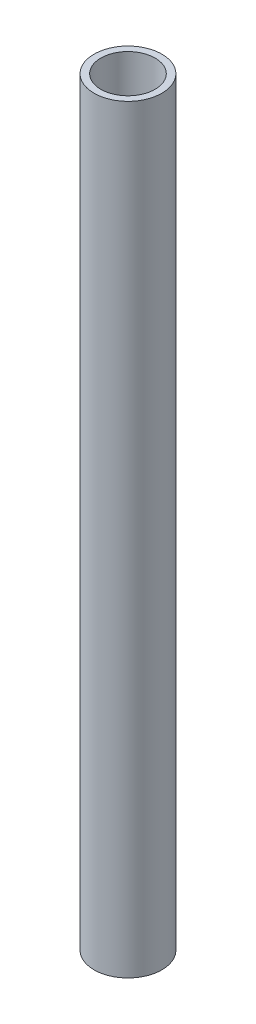
SolidWorks part; units mm, degrees
material "Сталь 08Х21Н5Т ГОСТ 5632-72"
ref_plane "Спереди" through (0, 0, 0) normal (0, 0, 1) x (1, 0, 0)
ref_plane "Сверху" through (0, 0, 0) normal (0, 1, 0) x (1, 0, 0)
ref_plane "Справа" through (0, 0, 0) normal (1, 0, 0) x (0, 0, -1)
other "Configuration Table"
sketch "Эскиз1" plane through (0, 0, 0) normal (0, 1, 0) x (1, 0, 0)
  circle A0 centre (0, 0) radius 4
  circle A1 centre (0, 0) radius 5
  dimension "D1" = 10
  dimension "D2" = 8
extrude "Бобышка-Вытянуть1" add sketch "Эскиз1" along normal blind 112
